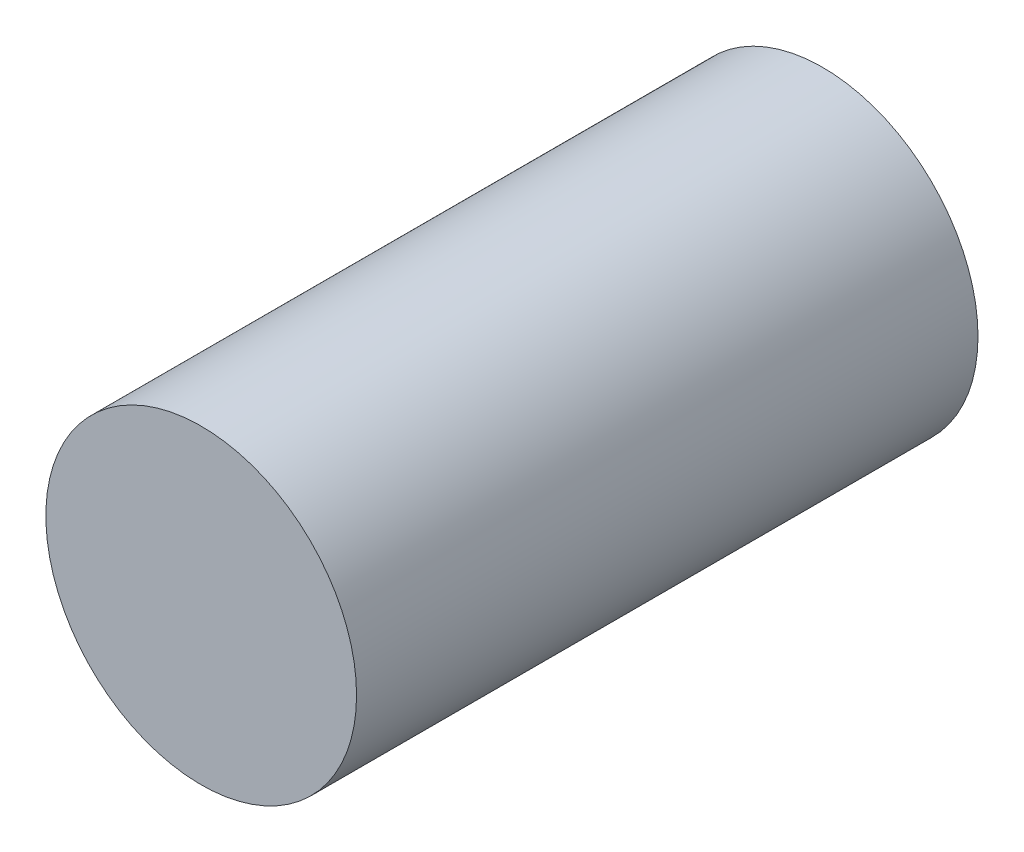
SolidWorks part; units mm, degrees
ref_plane "Front Plane" through (0, 0, 0) normal (0, 0, 1) x (1, 0, 0)
ref_plane "Top Plane" through (0, 0, 0) normal (0, 1, 0) x (1, 0, 0)
ref_plane "Right Plane" through (0, 0, 0) normal (1, 0, 0) x (0, 0, -1)
sketch "Sketch1" plane through (0, 0, 0) normal (0, 0, 1) x (1, 0, 0)
  circle A0 centre (0, 0) radius 12.7
  dimension "D1" = 25.4
extrude "Boss-Extrude1" add sketch "Sketch1" along normal blind 50.8
